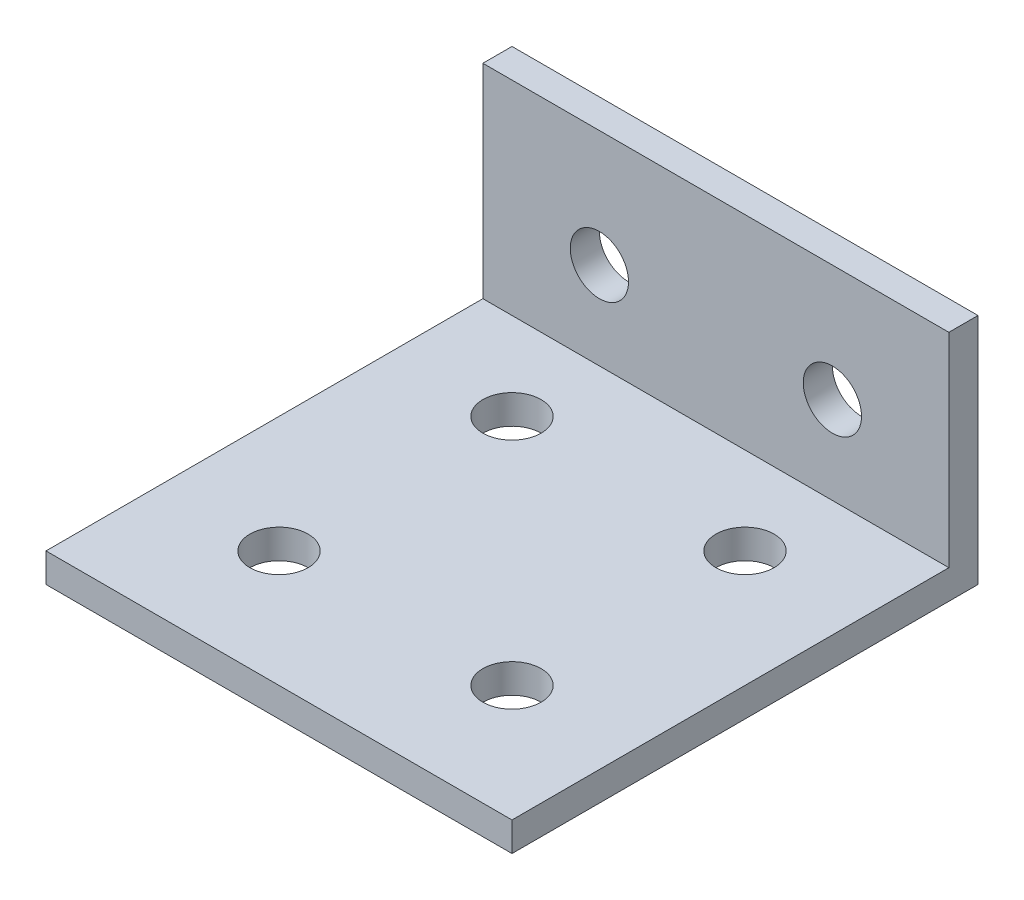
SolidWorks part; units mm, degrees
ref_plane "Front Plane" through (0, 0, 0) normal (0, 0, 1) x (1, 0, 0)
ref_plane "Top Plane" through (0, 0, 0) normal (0, 1, 0) x (1, 0, 0)
ref_plane "Right Plane" through (0, 0, 0) normal (1, 0, 0) x (0, 0, -1)
sketch "Sketch1" plane through (0, 0, 0) normal (0, 1, 0) x (1, 0, 0)
  line L0 (-25.4, 0) -> (25.4, 0) construction
  line L1 (-25.4, -25.4) -> (25.4, -25.4)
  line L2 (-25.4, -25.4) -> (-25.4, 25.4)
  line L3 (-25.4, 25.4) -> (25.4, 25.4)
  line L4 (25.4, -25.4) -> (25.4, 25.4)
  line L5 (-25.4, -25.4) -> (25.4, 25.4) construction
  line L6 (-25.4, 25.4) -> (25.4, -25.4) construction
  circle A0 centre (-12.7, -12.7) radius 3.175
  circle A1 centre (12.7, 12.7) radius 3.175
  circle A2 centre (12.7, -12.7) radius 3.175
  circle A3 centre (-12.7, 12.7) radius 3.175
  point P0 (0, 0)
  dimension "D3" = 6.35
  dimension "D4" = 12.7
  dimension "D1" = 50.8
  dimension "D2" = 50.8
extrude "Boss-Extrude1" add sketch "Sketch1" along normal blind 3.175
sketch "Sketch2" plane through (0, 3.175, 0) normal (0, 1, 0) x (1, 0, 0)
  line L0 (25.4, -25.4) -> (25.4, 25.4) construction
  line L1 (-25.4, 25.4) -> (25.4, 25.4)
  line L2 (-25.4, 25.4) -> (-25.4, 22.225)
  line L3 (-25.4, 22.225) -> (25.4, 22.225)
  line L4 (25.4, 25.4) -> (25.4, 22.225)
  dimension "D1" = 3.175
extrude "Boss-Extrude2" add sketch "Sketch2" along normal blind 22.225
sketch "Sketch3" plane through (0, 0, -22.225) normal (0, 0, 1) x (1, 0, 0)
  line L0 (0, 3.175) -> (0, 51.3094) construction
  line L1 (-25.4, 3.175) -> (25.4, 3.175) construction
  line L2 (-25.4, 25.4) -> (-25.4, 3.175) construction
  line L3 (-25.4, 25.4) -> (25.4, 25.4) construction
  circle A0 centre (-12.7, 12.7) radius 3.175
  circle A1 centre (12.7, 12.7) radius 3.175
  dimension "D1" = 6.35
  dimension "D2" = 12.7
  dimension "D3" = 12.7
extrude "Cut-Extrude1" cut sketch "Sketch3" against normal up to next
